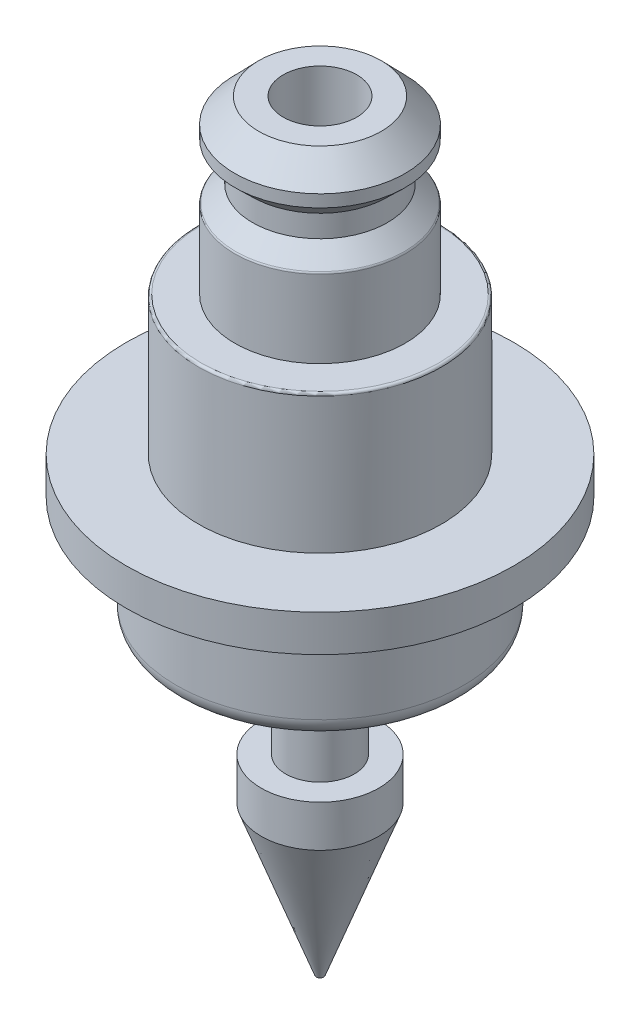
SolidWorks part; units mm, degrees
ref_plane "Front" through (0, 0, 0) normal (0, 0, 1) x (1, 0, 0)
ref_plane "Top" through (0, 0, 0) normal (0, 1, 0) x (1, 0, 0)
ref_plane "Right" through (0, 0, 0) normal (1, 0, 0) x (0, 0, -1)
sketch "Body Sketch" plane through (0, 0, 0) normal (0, 0, 1) x (1, 0, 0)
  line L0 (0, 0) -> (0, 14.15) construction
  line L1 (0, 14.15) -> (1.5, 14.15) construction
  line L2 (1.5, 14.15) -> (1.5, 0) construction
  line L3 (1.5, 0) -> (0, 0) construction
  line L4 (1.5, 14.15) -> (2.5, 14.15)
  line L5 (2.5, 14.15) -> (3.475, 13.15)
  line L6 (3.475, 13.15) -> (3.475, 12.65)
  line L7 (3.475, 12.65) -> (2.75, 11.95)
  line L8 (2.75, 11.95) -> (2.75, 11.05)
  line L9 (2.75, 11.05) -> (3.475, 10.35)
  line L10 (3.475, 10.35) -> (3.475, 7.15)
  line L11 (3.475, 7.15) -> (4.955, 7.15)
  line L12 (4.955, 7.15) -> (4.955, 1.5)
  line L13 (4.955, 1.5) -> (7.9, 1.5)
  line L14 (7.9, 1.5) -> (7.9, 0)
  line L15 (7.9, 0) -> (5.85, 0)
  line L16 (5.85, 0) -> (5.85, -4.5)
  line L17 (5.85, -4.5) -> (1.4, -4.5)
  line L18 (3.475, 12.65) -> (3.475, 10.35) construction
  line L19 (2.75, 11.5) -> (3.475, 11.5) construction
  line L20 (1.4, -4.5) -> (1.4, -9.1)
  line L21 (1.4, -9.1) -> (2.4, -9.1)
  line L22 (2.4, -9.1) -> (2.4, -10.8)
  line L23 (2.4, -10.8) -> (0.15, -16.9)
  line L24 (0.15, -16.9) -> (0.15, 0)
  line L25 (0.15, 0) -> (1.5, 0)
  line L26 (1.5, 0) -> (1.5, 14.15)
  dimension "D1" = 5
  dimension "D2" = 6.95
  dimension "D3" = 3
  dimension "D4" = 5.5
  dimension "D5" = 12.65
  dimension "D6" = 15.8
  dimension "D7" = 11.7
  dimension "D8" = 4.5
  dimension "D9" = 1.5
  dimension "D10" = 9.91
  dimension "D11" = 7
  dimension "D12" = 1
  dimension "D13" = 1.5
  dimension "D14" = 3.8
  dimension "D15" = 2.2
  dimension "D16" = 0.3
  dimension "D17" = 2.8
  dimension "D18" = 4.8
  dimension "D19" = 1.7
  dimension "D20" = 7.8
  dimension "D21" = 12.4
revolve "Body Revolve" add sketch "Body Sketch" angle 360 about L0
fillet "Green Base Fillet" radius 0.75 1 edges at (0, -4.5, -5.85)
fillet "Metal Top Fillets" radius 0.1 2 edges at (0, 10.35, -3.475) (0, 7.15, -4.955)
